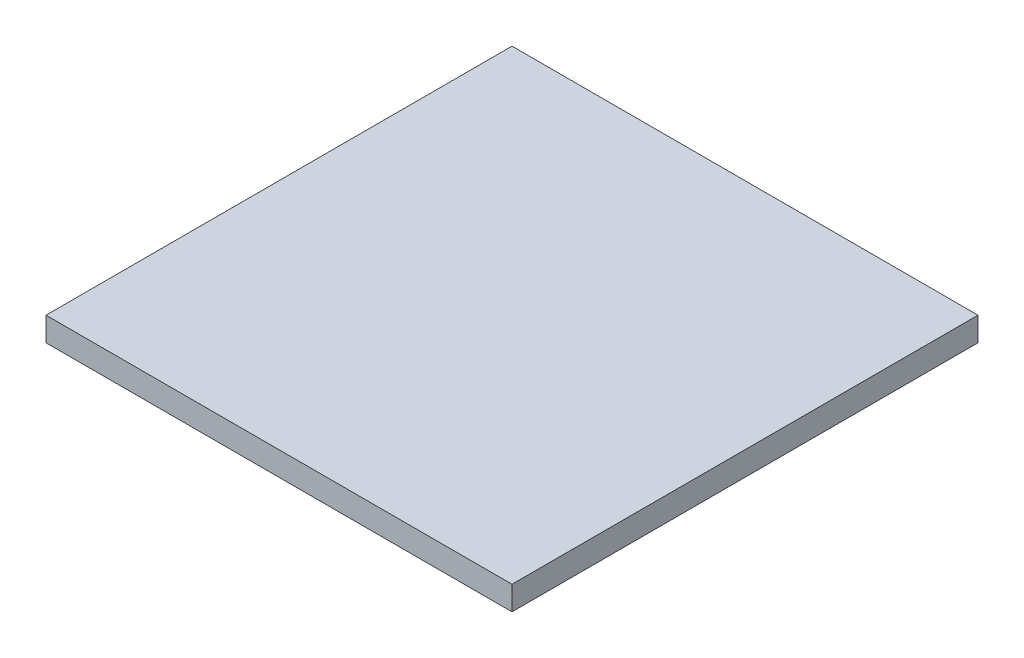
SolidWorks part; units mm, degrees
material "Pine"
ref_plane "Front Plane" through (0, 0, 0) normal (0, 0, 1) x (1, 0, 0)
ref_plane "Top Plane" through (0, 0, 0) normal (0, 1, 0) x (1, 0, 0)
ref_plane "Right Plane" through (0, 0, 0) normal (1, 0, 0) x (0, 0, -1)
sketch "Sketch1" plane through (0, 0, 0) normal (0, 1, 0) x (1, 0, 0)
  line L1 (-177.8, 177.8) -> (177.8, 177.8)
  line L2 (-177.8, 177.8) -> (-177.8, -177.8)
  line L3 (-177.8, -177.8) -> (177.8, -177.8)
  line L4 (177.8, 177.8) -> (177.8, -177.8)
  line L5 (0, -177.8) -> (0, 177.8) construction
  line L6 (-177.8, 0) -> (177.8, 0) construction
  point P0 (0, 0)
  dimension "D1" = 355.6
extrude "Boss-Extrude1" add sketch "Sketch1" along normal blind 18.2562
